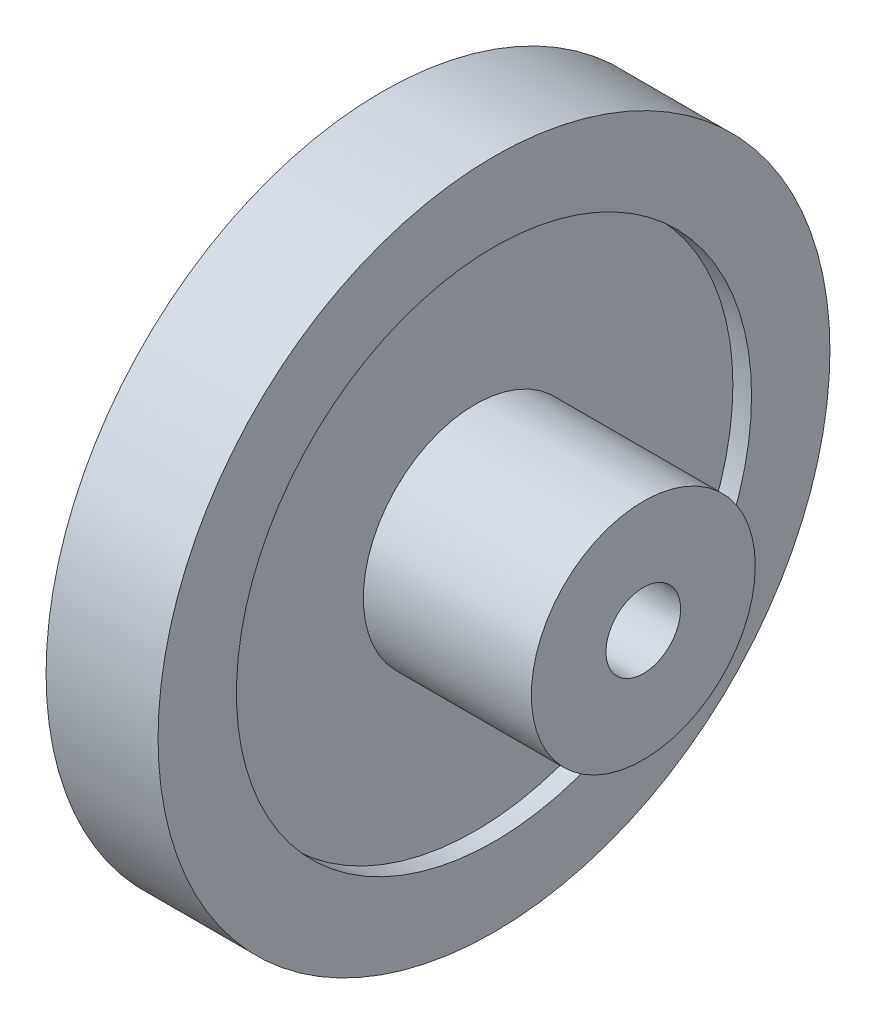
SolidWorks part; units mm, degrees
ref_plane "Plan de face" through (0, 0, 0) normal (0, 0, 1) x (1, 0, 0)
ref_plane "Plan de dessus" through (0, 0, 0) normal (0, 1, 0) x (1, 0, 0)
ref_plane "Plan de droite" through (0, 0, 0) normal (1, 0, 0) x (0, 0, -1)
sketch "Esquisse2" plane through (0, 0, 0) normal (1, 0, 0) x (0, 0, -1)
  arc A0 (8.9927, 0.363) -> (8.9699, 0.736) centre (0, 0) ccw
  arc A1 (8.7729, 2.0092) -> (8.6819, 2.3717) centre (0, 0) ccw
  arc A2 (8.2543, 3.587) -> (8.0983, 3.9266) centre (0, 0) ccw
  arc A3 (7.4547, 5.0426) -> (7.2389, 5.3478) centre (0, 0) ccw
  arc A4 (6.4012, 6.3266) -> (6.133, 6.5869) centre (0, 0) ccw
  arc A5 (5.1297, 7.395) -> (4.8182, 7.6016) centre (0, 0) ccw
  arc A6 (3.6835, 8.2117) -> (3.3394, 8.3575) centre (0, 0) ccw
  arc A7 (2.1119, 8.7487) -> (1.7468, 8.8289) centre (0, 0) ccw
  arc A8 (0.4683, 8.9878) -> (0.0948, 8.9995) centre (0, 0) ccw
  arc A9 (-1.1911, 8.9208) -> (-1.5605, 8.8637) centre (0, 0) ccw
  arc A10 (-2.8101, 8.5501) -> (-3.1626, 8.426) centre (0, 0) ccw
  arc A11 (-4.3333, 7.8881) -> (-4.657, 7.7014) centre (0, 0) ccw
  arc A12 (-5.7089, 6.9576) -> (-5.9929, 6.7146) centre (0, 0) ccw
  arc A13 (-6.8902, 5.7901) -> (-7.1246, 5.499) centre (0, 0) ccw
  arc A14 (-7.8368, 4.4254) -> (-8.0138, 4.0963) centre (0, 0) ccw
  arc A15 (-8.5165, 2.9101) -> (-8.63, 2.554) centre (0, 0) ccw
  arc A16 (-8.9063, 1.2956) -> (-8.9524, 0.9247) centre (0, 0) ccw
  arc A17 (-8.9927, -0.363) -> (-8.9699, -0.736) centre (0, 0) ccw
  arc A18 (-8.7729, -2.0092) -> (-8.6819, -2.3717) centre (0, 0) ccw
  arc A19 (-8.2543, -3.587) -> (-8.0983, -3.9266) centre (0, 0) ccw
  arc A20 (-7.4547, -5.0426) -> (-7.2389, -5.3478) centre (0, 0) ccw
  arc A21 (-6.4012, -6.3266) -> (-6.133, -6.5869) centre (0, 0) ccw
  arc A22 (-5.1297, -7.395) -> (-4.8182, -7.6016) centre (0, 0) ccw
  arc A23 (-3.6835, -8.2117) -> (-3.3394, -8.3575) centre (0, 0) ccw
  arc A24 (-2.1119, -8.7487) -> (-1.7468, -8.8289) centre (0, 0) ccw
  arc A25 (-0.4683, -8.9878) -> (-0.0948, -8.9995) centre (0, 0) ccw
  arc A26 (1.1911, -8.9208) -> (1.5605, -8.8637) centre (0, 0) ccw
  arc A27 (2.8101, -8.5501) -> (3.1626, -8.426) centre (0, 0) ccw
  arc A28 (4.3333, -7.8881) -> (4.657, -7.7014) centre (0, 0) ccw
  arc A29 (5.7089, -6.9576) -> (5.9929, -6.7146) centre (0, 0) ccw
  arc A30 (6.8902, -5.7901) -> (7.1246, -5.499) centre (0, 0) ccw
  arc A31 (7.8368, -4.4254) -> (8.0138, -4.0963) centre (0, 0) ccw
  arc A32 (8.5165, -2.9101) -> (8.63, -2.554) centre (0, 0) ccw
  arc A33 (8.9063, -1.2956) -> (8.9524, -0.9247) centre (0, 0) ccw
  arc A34 (7.987, 0) -> (7.8742, -0.1109) centre (7.9867, -0.1125) ccw
  arc A35 (7.8657, -0.3818) -> (7.9719, -0.4996) centre (7.9781, -0.3873) ccw
  arc A36 (7.8657, -0.3818) -> (7.8742, -0.1109) centre (0, 0) ccw
  arc A37 (7.851, 1.4676) -> (7.7605, 1.3379) centre (7.8714, 1.357) ccw
  arc A38 (7.802, 1.07) -> (7.928, 0.9737) centre (7.9134, 1.0853) ccw
  arc A39 (7.802, 1.07) -> (7.7605, 1.3379) centre (0, 0) ccw
  arc A40 (7.4477, 2.8852) -> (7.3826, 2.7411) centre (7.488, 2.7802) ccw
  arc A41 (7.4725, 2.4854) -> (7.6141, 2.4139) centre (7.5793, 2.5209) ccw
  arc A42 (7.4725, 2.4854) -> (7.3826, 2.7411) centre (0, 0) ccw
  arc A43 (6.7907, 4.2046) -> (6.7532, 4.0509) centre (6.8497, 4.1088) ccw
  arc A44 (6.8886, 3.8161) -> (7.0409, 3.7719) centre (6.987, 3.8706) ccw
  arc A45 (6.8886, 3.8161) -> (6.7532, 4.0509) centre (0, 0) ccw
  arc A46 (5.9025, 5.3808) -> (5.8938, 5.2229) centre (5.978, 5.2975) ccw
  arc A47 (6.0701, 5.0169) -> (6.2279, 5.0014) centre (6.1568, 5.0886) ccw
  arc A48 (6.0701, 5.0169) -> (5.8938, 5.2229) centre (0, 0) ccw
  arc A49 (4.8132, 6.3738) -> (4.8338, 6.2169) centre (4.9028, 6.3057) ccw
  arc A50 (5.0449, 6.0469) -> (5.2029, 6.0607) centre (5.117, 6.1333) ccw
  arc A51 (5.0449, 6.0469) -> (4.8338, 6.2169) centre (0, 0) ccw
  arc A52 (3.5601, 7.1497) -> (3.6091, 6.9993) centre (3.6607, 7.0993) ccw
  arc A53 (3.8479, 6.8709) -> (4.0007, 6.9135) centre (3.9028, 6.9691) ccw
  arc A54 (3.8479, 6.8709) -> (3.6091, 6.9993) centre (0, 0) ccw
  arc A55 (2.1857, 7.6821) -> (2.2616, 7.5433) centre (2.2939, 7.651) ccw
  arc A56 (2.5198, 7.461) -> (2.6622, 7.5309) centre (2.5558, 7.5676) ccw
  arc A57 (2.5198, 7.461) -> (2.2616, 7.5433) centre (0, 0) ccw
  arc A58 (0.7369, 7.9529) -> (0.837, 7.8304) centre (0.8489, 7.9423) ccw
  arc A59 (1.106, 7.797) -> (1.2331, 7.8918) centre (1.1218, 7.9083) ccw
  arc A60 (1.106, 7.797) -> (0.837, 7.8304) centre (0, 0) ccw
  arc A61 (-0.7369, 7.9529) -> (-0.6161, 7.8509) centre (-0.6249, 7.963) ccw
  arc A62 (-0.3455, 7.8674) -> (-0.2381, 7.984) centre (-0.3505, 7.9798) ccw
  arc A63 (-0.3455, 7.8674) -> (-0.6161, 7.8509) centre (0, 0) ccw
  arc A64 (-2.1857, 7.6821) -> (-2.0482, 7.604) centre (-2.0775, 7.7126) ccw
  arc A65 (-1.7853, 7.67) -> (-1.7011, 7.8044) centre (-1.8108, 7.7795) ccw
  arc A66 (-1.7853, 7.67) -> (-2.0482, 7.604) centre (0, 0) ccw
  arc A67 (-3.5601, 7.1497) -> (-3.4106, 7.0981) centre (-3.4593, 7.1996) ccw
  arc A68 (-3.1642, 7.2113) -> (-3.1062, 7.3589) centre (-3.2095, 7.3143) ccw
  arc A69 (-3.1642, 7.2113) -> (-3.4106, 7.0981) centre (0, 0) ccw
  arc A70 (-4.8132, 6.3738) -> (-4.6568, 6.3506) centre (-4.7233, 6.4413) ccw
  arc A71 (-4.4354, 6.5071) -> (-4.4055, 6.6628) centre (-4.4988, 6.6001) ccw
  arc A72 (-4.4354, 6.5071) -> (-4.6568, 6.3506) centre (0, 0) ccw
  arc A73 (-5.9025, 5.3808) -> (-5.7444, 5.3868) centre (-5.8265, 5.4637) ccw
  arc A74 (-5.5556, 5.5813) -> (-5.5547, 5.7399) centre (-5.635, 5.661) ccw
  arc A75 (-5.5556, 5.5813) -> (-5.7444, 5.3868) centre (0, 0) ccw
  arc A76 (-6.7907, 4.2046) -> (-6.6364, 4.2395) centre (-6.7312, 4.3001) ccw
  arc A77 (-6.4866, 4.4654) -> (-6.5149, 4.6215) centre (-6.5792, 4.5292) ccw
  arc A78 (-6.4866, 4.4654) -> (-6.6364, 4.2395) centre (0, 0) ccw
  arc A79 (-7.4477, 2.8852) -> (-7.3024, 2.9479) centre (-7.4067, 2.99) ccw
  arc A80 (-7.1966, 3.1975) -> (-7.2531, 3.3457) centre (-7.2995, 3.2432) ccw
  arc A81 (-7.1966, 3.1975) -> (-7.3024, 2.9479) centre (0, 0) ccw
  arc A82 (-7.851, 1.4676) -> (-7.7198, 1.5559) centre (-7.83, 1.5781) ccw
  arc A83 (-7.6616, 1.8207) -> (-7.7444, 1.956) centre (-7.7711, 1.8467) ccw
  arc A84 (-7.6616, 1.8207) -> (-7.7198, 1.5559) centre (0, 0) ccw
  arc A85 (-7.987, 0) -> (-7.8742, 0.1109) centre (-7.9867, 0.1125) ccw
  arc A86 (-7.8657, 0.3818) -> (-7.9719, 0.4996) centre (-7.9781, 0.3873) ccw
  arc A87 (-7.8657, 0.3818) -> (-7.8742, 0.1109) centre (0, 0) ccw
  arc A88 (-7.851, -1.4676) -> (-7.7605, -1.3379) centre (-7.8714, -1.357) ccw
  arc A89 (-7.802, -1.07) -> (-7.928, -0.9737) centre (-7.9134, -1.0853) ccw
  arc A90 (-7.802, -1.07) -> (-7.7605, -1.3379) centre (0, 0) ccw
  arc A91 (-7.4477, -2.8852) -> (-7.3826, -2.7411) centre (-7.488, -2.7802) ccw
  arc A92 (-7.4725, -2.4854) -> (-7.6141, -2.4139) centre (-7.5793, -2.5209) ccw
  arc A93 (-7.4725, -2.4854) -> (-7.3826, -2.7411) centre (0, 0) ccw
  arc A94 (-6.7907, -4.2046) -> (-6.7532, -4.0509) centre (-6.8497, -4.1088) ccw
  arc A95 (-6.8886, -3.8161) -> (-7.0409, -3.7719) centre (-6.987, -3.8706) ccw
  arc A96 (-6.8886, -3.8161) -> (-6.7532, -4.0509) centre (0, 0) ccw
  arc A97 (-5.9025, -5.3808) -> (-5.8938, -5.2229) centre (-5.978, -5.2975) ccw
  arc A98 (-6.0701, -5.0169) -> (-6.2279, -5.0014) centre (-6.1568, -5.0886) ccw
  arc A99 (-6.0701, -5.0169) -> (-5.8938, -5.2229) centre (0, 0) ccw
  arc A100 (-4.8132, -6.3738) -> (-4.8338, -6.2169) centre (-4.9028, -6.3057) ccw
  arc A101 (-5.0449, -6.0469) -> (-5.2029, -6.0607) centre (-5.117, -6.1333) ccw
  arc A102 (-5.0449, -6.0469) -> (-4.8338, -6.2169) centre (0, 0) ccw
  arc A103 (-3.5601, -7.1497) -> (-3.6091, -6.9993) centre (-3.6607, -7.0993) ccw
  arc A104 (-3.8479, -6.8709) -> (-4.0007, -6.9135) centre (-3.9028, -6.9691) ccw
  arc A105 (-3.8479, -6.8709) -> (-3.6091, -6.9993) centre (0, 0) ccw
  arc A106 (-2.1857, -7.6821) -> (-2.2616, -7.5433) centre (-2.2939, -7.651) ccw
  arc A107 (-2.5198, -7.461) -> (-2.6622, -7.5309) centre (-2.5558, -7.5676) ccw
  arc A108 (-2.5198, -7.461) -> (-2.2616, -7.5433) centre (0, 0) ccw
  arc A109 (-0.7369, -7.9529) -> (-0.837, -7.8304) centre (-0.8489, -7.9423) ccw
  arc A110 (-1.106, -7.797) -> (-1.2331, -7.8918) centre (-1.1218, -7.9083) ccw
  arc A111 (-1.106, -7.797) -> (-0.837, -7.8304) centre (0, 0) ccw
  arc A112 (0.7369, -7.9529) -> (0.6161, -7.8509) centre (0.6249, -7.963) ccw
  arc A113 (0.3455, -7.8674) -> (0.2381, -7.984) centre (0.3505, -7.9798) ccw
  arc A114 (0.3455, -7.8674) -> (0.6161, -7.8509) centre (0, 0) ccw
  arc A115 (2.1857, -7.6821) -> (2.0482, -7.604) centre (2.0775, -7.7126) ccw
  arc A116 (1.7853, -7.67) -> (1.7011, -7.8044) centre (1.8108, -7.7795) ccw
  arc A117 (1.7853, -7.67) -> (2.0482, -7.604) centre (0, 0) ccw
  arc A118 (3.5601, -7.1497) -> (3.4106, -7.0981) centre (3.4593, -7.1996) ccw
  arc A119 (3.1642, -7.2113) -> (3.1062, -7.3589) centre (3.2095, -7.3143) ccw
  arc A120 (3.1642, -7.2113) -> (3.4106, -7.0981) centre (0, 0) ccw
  arc A121 (4.8132, -6.3738) -> (4.6568, -6.3506) centre (4.7233, -6.4413) ccw
  arc A122 (4.4354, -6.5071) -> (4.4055, -6.6628) centre (4.4988, -6.6001) ccw
  arc A123 (4.4354, -6.5071) -> (4.6568, -6.3506) centre (0, 0) ccw
  arc A124 (5.9025, -5.3808) -> (5.7444, -5.3868) centre (5.8265, -5.4637) ccw
  arc A125 (5.5556, -5.5813) -> (5.5547, -5.7399) centre (5.635, -5.661) ccw
  arc A126 (5.5556, -5.5813) -> (5.7444, -5.3868) centre (0, 0) ccw
  arc A127 (6.7907, -4.2046) -> (6.6364, -4.2395) centre (6.7312, -4.3001) ccw
  arc A128 (6.4866, -4.4654) -> (6.5149, -4.6215) centre (6.5792, -4.5292) ccw
  arc A129 (6.4866, -4.4654) -> (6.6364, -4.2395) centre (0, 0) ccw
  arc A130 (7.4477, -2.8852) -> (7.3024, -2.9479) centre (7.4067, -2.99) ccw
  arc A131 (7.1966, -3.1975) -> (7.2531, -3.3457) centre (7.2995, -3.2432) ccw
  arc A132 (7.1966, -3.1975) -> (7.3024, -2.9479) centre (0, 0) ccw
  arc A133 (7.851, -1.4676) -> (7.7198, -1.5559) centre (7.83, -1.5781) ccw
  arc A134 (7.6616, -1.8207) -> (7.7444, -1.956) centre (7.7711, -1.8467) ccw
  arc A135 (7.6616, -1.8207) -> (7.7198, -1.5559) centre (0, 0) ccw
  circle A136 centre (0, 0) radius 1
  spline S0 degree 3 poles (7.987, 0) (8.0286, 0) (8.2037, 0.0282) (8.4818, 0.1115) (8.7713, 0.2415) (8.9323, 0.3284) (8.9927, 0.363) knots 0 0 0 0 0.124841 0.528779 0.867842 1.076016 1.076016 1.076016 1.076016
  spline S1 degree 3 poles (7.928, 0.9737) (7.9687, 0.9787) (8.146, 0.9721) (8.4321, 0.9233) (8.7354, 0.8295) (8.9058, 0.7629) (8.9699, 0.736) knots 0 0 0 0 0.124841 0.528779 0.867842 1.076016 1.076016 1.076016 1.076016
  spline S2 degree 3 poles (7.851, 1.4676) (7.8919, 1.4753) (8.0589, 1.5352) (8.3169, 1.6682) (8.5776, 1.8491) (8.7199, 1.9642) (8.7729, 2.0092) knots 0 0 0 0 0.124841 0.528779 0.867842 1.076016 1.076016 1.076016 1.076016
  spline S3 degree 3 poles (7.6141, 2.4139) (7.6532, 2.4263) (7.8287, 2.4523) (8.1189, 2.4569) (8.4342, 2.4205) (8.6139, 2.3863) (8.6819, 2.3717) knots 0 0 0 0 0.124841 0.528779 0.867842 1.076016 1.076016 1.076016 1.076016
  spline S4 degree 3 poles (7.4477, 2.8852) (7.4865, 2.9003) (7.6396, 2.9898) (7.8687, 3.168) (8.0918, 3.3938) (8.2105, 3.533) (8.2543, 3.587) knots 0 0 0 0 0.124841 0.528779 0.867842 1.076016 1.076016 1.076016 1.076016
  spline S5 degree 3 poles (7.0409, 3.7719) (7.0771, 3.7913) (7.2448, 3.8491) (7.5292, 3.9069) (7.8458, 3.9291) (8.0288, 3.9285) (8.0983, 3.9266) knots 0 0 0 0 0.124841 0.528779 0.867842 1.076016 1.076016 1.076016 1.076016
  spline S6 degree 3 poles (6.7907, 4.2046) (6.8261, 4.2265) (6.9601, 4.3427) (7.1526, 4.5599) (7.3304, 4.8229) (7.4215, 4.9815) (7.4547, 5.0426) knots 0 0 0 0 0.124841 0.528779 0.867842 1.076016 1.076016 1.076016 1.076016
  spline S7 degree 3 poles (6.2279, 5.0014) (6.2599, 5.0271) (6.4141, 5.1148) (6.6831, 5.2239) (6.9903, 5.3039) (7.1702, 5.3369) (7.2389, 5.3478) knots 0 0 0 0 0.124841 0.528779 0.867842 1.076016 1.076016 1.076016 1.076016
  spline S8 degree 3 poles (5.9025, 5.3808) (5.9332, 5.4088) (6.0436, 5.5477) (6.193, 5.7966) (6.3194, 6.0877) (6.3798, 6.2604) (6.4012, 6.3266) knots 0 0 0 0 0.124841 0.528779 0.867842 1.076016 1.076016 1.076016 1.076016
  spline S9 degree 3 poles (5.2029, 6.0607) (5.2296, 6.0918) (5.3651, 6.2063) (5.6094, 6.363) (5.8967, 6.498) (6.0675, 6.5636) (6.133, 6.5869) knots 0 0 0 0 0.124841 0.528779 0.867842 1.076016 1.076016 1.076016 1.076016
  spline S10 degree 3 poles (4.8132, 6.3738) (4.8383, 6.407) (4.9213, 6.5637) (5.0224, 6.8358) (5.0932, 7.1452) (5.1208, 7.3261) (5.1297, 7.395) knots 0 0 0 0 0.124841 0.528779 0.867842 1.076016 1.076016 1.076016 1.076016
  spline S11 degree 3 poles (4.0007, 6.9135) (4.0212, 6.949) (4.1333, 7.0864) (4.3447, 7.2854) (4.6022, 7.4709) (4.7581, 7.5667) (4.8182, 7.6016) knots 0 0 0 0 0.124841 0.528779 0.867842 1.076016 1.076016 1.076016 1.076016
  spline S12 degree 3 poles (3.5601, 7.1497) (3.5787, 7.1869) (3.6315, 7.3563) (3.6808, 7.6423) (3.6935, 7.9594) (3.6875, 8.1423) (3.6835, 8.2117) knots 0 0 0 0 0.124841 0.528779 0.867842 1.076016 1.076016 1.076016 1.076016
  spline S13 degree 3 poles (2.6622, 7.5309) (2.6759, 7.5696) (2.7608, 7.7253) (2.932, 7.9596) (3.1511, 8.1893) (3.2867, 8.3122) (3.3394, 8.3575) knots 0 0 0 0 0.124841 0.528779 0.867842 1.076016 1.076016 1.076016 1.076016
  spline S14 degree 3 poles (2.1857, 7.6821) (2.1971, 7.7221) (2.2179, 7.8983) (2.2139, 8.1885) (2.1681, 8.5026) (2.1286, 8.6812) (2.1119, 8.7487) knots 0 0 0 0 0.124841 0.528779 0.867842 1.076016 1.076016 1.076016 1.076016
  spline S15 degree 3 poles (1.2331, 7.8918) (1.2394, 7.9324) (1.2943, 8.101) (1.4195, 8.3629) (1.5927, 8.6289) (1.7034, 8.7746) (1.7468, 8.8289) knots 0 0 0 0 0.124841 0.528779 0.867842 1.076016 1.076016 1.076016 1.076016
  spline S16 degree 3 poles (0.7369, 7.9529) (0.7408, 7.9944) (0.7288, 8.1713) (0.6715, 8.4559) (0.5688, 8.7562) (0.4971, 8.9245) (0.4683, 8.9878) knots 0 0 0 0 0.124841 0.528779 0.867842 1.076016 1.076016 1.076016 1.076016
  spline S17 degree 3 poles (-0.2381, 7.984) (-0.2393, 8.025) (-0.2163, 8.2009) (-0.1413, 8.4813) (-0.02, 8.7746) (0.0621, 8.9382) (0.0948, 8.9995) knots 0 0 0 0 0.124841 0.528779 0.867842 1.076016 1.076016 1.076016 1.076016
  spline S18 degree 3 poles (-0.7369, 7.9529) (-0.7408, 7.9944) (-0.785, 8.1661) (-0.8937, 8.4353) (-1.0498, 8.7116) (-1.1512, 8.8639) (-1.1911, 8.9208) knots 0 0 0 0 0.124841 0.528779 0.867842 1.076016 1.076016 1.076016 1.076016
  spline S19 degree 3 poles (-1.7011, 7.8044) (-1.7098, 7.8444) (-1.7195, 8.0216) (-1.6973, 8.311) (-1.632, 8.6216) (-1.5814, 8.7974) (-1.5605, 8.8637) knots 0 0 0 0 0.124841 0.528779 0.867842 1.076016 1.076016 1.076016 1.076016
  spline S20 degree 3 poles (-2.1857, 7.6821) (-2.1971, 7.7221) (-2.2722, 7.8828) (-2.4284, 8.1275) (-2.6327, 8.3704) (-2.7603, 8.5015) (-2.8101, 8.5501) knots 0 0 0 0 0.124841 0.528779 0.867842 1.076016 1.076016 1.076016 1.076016
  spline S21 degree 3 poles (-3.1062, 7.3589) (-3.1221, 7.3967) (-3.1642, 7.569) (-3.1956, 7.8576) (-3.1884, 8.1749) (-3.171, 8.357) (-3.1626, 8.426) knots 0 0 0 0 0.124841 0.528779 0.867842 1.076016 1.076016 1.076016 1.076016
  spline S22 degree 3 poles (-3.5601, 7.1497) (-3.5787, 7.1869) (-3.682, 7.3311) (-3.8805, 7.5429) (-4.1259, 7.7441) (-4.2755, 7.8495) (-4.3333, 7.8881) knots 0 0 0 0 0.124841 0.528779 0.867842 1.076016 1.076016 1.076016 1.076016
  spline S23 degree 3 poles (-4.4055, 6.6628) (-4.4281, 6.6971) (-4.5011, 6.8587) (-4.585, 7.1366) (-4.6363, 7.4498) (-4.6526, 7.6321) (-4.657, 7.7014) knots 0 0 0 0 0.124841 0.528779 0.867842 1.076016 1.076016 1.076016 1.076016
  spline S24 degree 3 poles (-4.8132, 6.3738) (-4.8383, 6.407) (-4.9664, 6.5297) (-5.2004, 6.7014) (-5.4787, 6.8541) (-5.645, 6.9302) (-5.7089, 6.9576) knots 0 0 0 0 0.124841 0.528779 0.867842 1.076016 1.076016 1.076016 1.076016
  spline S25 degree 3 poles (-5.5547, 5.7399) (-5.5833, 5.7694) (-5.6848, 5.9148) (-5.8183, 6.1726) (-5.9262, 6.4711) (-5.9757, 6.6472) (-5.9929, 6.7146) knots 0 0 0 0 0.124841 0.528779 0.867842 1.076016 1.076016 1.076016 1.076016
  spline S26 degree 3 poles (-5.9025, 5.3808) (-5.9332, 5.4088) (-6.0816, 5.506) (-6.3432, 5.6317) (-6.6448, 5.7307) (-6.8223, 5.775) (-6.8902, 5.7901) knots 0 0 0 0 0.124841 0.528779 0.867842 1.076016 1.076016 1.076016 1.076016
  spline S27 degree 3 poles (-6.5149, 4.6215) (-6.5483, 4.6452) (-6.6748, 4.7696) (-6.8534, 4.9984) (-7.0144, 5.2719) (-7.0954, 5.436) (-7.1246, 5.499) knots 0 0 0 0 0.124841 0.528779 0.867842 1.076016 1.076016 1.076016 1.076016
  spline S28 degree 3 poles (-6.7907, 4.2046) (-6.8261, 4.2265) (-6.9898, 4.2947) (-7.2701, 4.3703) (-7.5847, 4.4122) (-7.7673, 4.423) (-7.8368, 4.4254) knots 0 0 0 0 0.124841 0.528779 0.867842 1.076016 1.076016 1.076016 1.076016
  spline S29 degree 3 poles (-7.2531, 3.3457) (-7.2904, 3.3629) (-7.4376, 3.4619) (-7.6552, 3.654) (-7.8637, 3.8933) (-7.9735, 4.0396) (-8.0138, 4.0963) knots 0 0 0 0 0.124841 0.528779 0.867842 1.076016 1.076016 1.076016 1.076016
  spline S30 degree 3 poles (-7.4477, 2.8852) (-7.4865, 2.9003) (-7.66, 2.9372) (-7.9493, 2.96) (-8.2663, 2.9434) (-8.4478, 2.9205) (-8.5165, 2.9101) knots 0 0 0 0 0.124841 0.528779 0.867842 1.076016 1.076016 1.076016 1.076016
  spline S31 degree 3 poles (-7.7444, 1.956) (-7.7842, 1.966) (-7.9471, 2.0363) (-8.1962, 2.1851) (-8.4452, 2.3821) (-8.58, 2.5057) (-8.63, 2.554) knots 0 0 0 0 0.124841 0.528779 0.867842 1.076016 1.076016 1.076016 1.076016
  spline S32 degree 3 poles (-7.851, 1.4676) (-7.8919, 1.4753) (-8.0692, 1.4797) (-8.3578, 1.4489) (-8.6664, 1.3743) (-8.8406, 1.3185) (-8.9063, 1.2956) knots 0 0 0 0 0.124841 0.528779 0.867842 1.076016 1.076016 1.076016 1.076016
  spline S33 degree 3 poles (-7.9719, 0.4996) (-8.0129, 0.5022) (-8.1859, 0.5413) (-8.4582, 0.6419) (-8.7391, 0.7897) (-8.8943, 0.8865) (-8.9524, 0.9247) knots 0 0 0 0 0.124841 0.528779 0.867842 1.076016 1.076016 1.076016 1.076016
  spline S34 degree 3 poles (-7.987, 0) (-8.0286, 0) (-8.2037, -0.0282) (-8.4818, -0.1115) (-8.7713, -0.2415) (-8.9323, -0.3284) (-8.9927, -0.363) knots 0 0 0 0 0.124841 0.528779 0.867842 1.076016 1.076016 1.076016 1.076016
  spline S35 degree 3 poles (-7.928, -0.9737) (-7.9687, -0.9787) (-8.146, -0.9721) (-8.4321, -0.9233) (-8.7354, -0.8295) (-8.9058, -0.7629) (-8.9699, -0.736) knots 0 0 0 0 0.124841 0.528779 0.867842 1.076016 1.076016 1.076016 1.076016
  spline S36 degree 3 poles (-7.851, -1.4676) (-7.8919, -1.4753) (-8.0589, -1.5352) (-8.3169, -1.6682) (-8.5776, -1.8491) (-8.7199, -1.9642) (-8.7729, -2.0092) knots 0 0 0 0 0.124841 0.528779 0.867842 1.076016 1.076016 1.076016 1.076016
  spline S37 degree 3 poles (-7.6141, -2.4139) (-7.6532, -2.4263) (-7.8287, -2.4523) (-8.1189, -2.4569) (-8.4342, -2.4205) (-8.6139, -2.3863) (-8.6819, -2.3717) knots 0 0 0 0 0.124841 0.528779 0.867842 1.076016 1.076016 1.076016 1.076016
  spline S38 degree 3 poles (-7.4477, -2.8852) (-7.4865, -2.9003) (-7.6396, -2.9898) (-7.8687, -3.168) (-8.0918, -3.3938) (-8.2105, -3.533) (-8.2543, -3.587) knots 0 0 0 0 0.124841 0.528779 0.867842 1.076016 1.076016 1.076016 1.076016
  spline S39 degree 3 poles (-7.0409, -3.7719) (-7.0771, -3.7913) (-7.2448, -3.8491) (-7.5292, -3.9069) (-7.8458, -3.9291) (-8.0288, -3.9285) (-8.0983, -3.9266) knots 0 0 0 0 0.124841 0.528779 0.867842 1.076016 1.076016 1.076016 1.076016
  spline S40 degree 3 poles (-6.7907, -4.2046) (-6.8261, -4.2265) (-6.9601, -4.3427) (-7.1526, -4.5599) (-7.3304, -4.8229) (-7.4215, -4.9815) (-7.4547, -5.0426) knots 0 0 0 0 0.124841 0.528779 0.867842 1.076016 1.076016 1.076016 1.076016
  spline S41 degree 3 poles (-6.2279, -5.0014) (-6.2599, -5.0271) (-6.4141, -5.1148) (-6.6831, -5.2239) (-6.9903, -5.3039) (-7.1702, -5.3369) (-7.2389, -5.3478) knots 0 0 0 0 0.124841 0.528779 0.867842 1.076016 1.076016 1.076016 1.076016
  spline S42 degree 3 poles (-5.9025, -5.3808) (-5.9332, -5.4088) (-6.0436, -5.5477) (-6.193, -5.7966) (-6.3194, -6.0877) (-6.3798, -6.2604) (-6.4012, -6.3266) knots 0 0 0 0 0.124841 0.528779 0.867842 1.076016 1.076016 1.076016 1.076016
  spline S43 degree 3 poles (-5.2029, -6.0607) (-5.2296, -6.0918) (-5.3651, -6.2063) (-5.6094, -6.363) (-5.8967, -6.498) (-6.0675, -6.5636) (-6.133, -6.5869) knots 0 0 0 0 0.124841 0.528779 0.867842 1.076016 1.076016 1.076016 1.076016
  spline S44 degree 3 poles (-4.8132, -6.3738) (-4.8383, -6.407) (-4.9213, -6.5637) (-5.0224, -6.8358) (-5.0932, -7.1452) (-5.1208, -7.3261) (-5.1297, -7.395) knots 0 0 0 0 0.124841 0.528779 0.867842 1.076016 1.076016 1.076016 1.076016
  spline S45 degree 3 poles (-4.0007, -6.9135) (-4.0212, -6.949) (-4.1333, -7.0864) (-4.3447, -7.2854) (-4.6022, -7.4709) (-4.7581, -7.5667) (-4.8182, -7.6016) knots 0 0 0 0 0.124841 0.528779 0.867842 1.076016 1.076016 1.076016 1.076016
  spline S46 degree 3 poles (-3.5601, -7.1497) (-3.5787, -7.1869) (-3.6315, -7.3563) (-3.6808, -7.6423) (-3.6935, -7.9594) (-3.6875, -8.1423) (-3.6835, -8.2117) knots 0 0 0 0 0.124841 0.528779 0.867842 1.076016 1.076016 1.076016 1.076016
  spline S47 degree 3 poles (-2.6622, -7.5309) (-2.6759, -7.5696) (-2.7608, -7.7253) (-2.932, -7.9596) (-3.1511, -8.1893) (-3.2867, -8.3122) (-3.3394, -8.3575) knots 0 0 0 0 0.124841 0.528779 0.867842 1.076016 1.076016 1.076016 1.076016
  spline S48 degree 3 poles (-2.1857, -7.6821) (-2.1971, -7.7221) (-2.2179, -7.8983) (-2.2139, -8.1885) (-2.1681, -8.5026) (-2.1286, -8.6812) (-2.1119, -8.7487) knots 0 0 0 0 0.124841 0.528779 0.867842 1.076016 1.076016 1.076016 1.076016
  spline S49 degree 3 poles (-1.2331, -7.8918) (-1.2394, -7.9324) (-1.2943, -8.101) (-1.4195, -8.3629) (-1.5927, -8.6289) (-1.7034, -8.7746) (-1.7468, -8.8289) knots 0 0 0 0 0.124841 0.528779 0.867842 1.076016 1.076016 1.076016 1.076016
  spline S50 degree 3 poles (-0.7369, -7.9529) (-0.7408, -7.9944) (-0.7288, -8.1713) (-0.6715, -8.4559) (-0.5688, -8.7562) (-0.4971, -8.9245) (-0.4683, -8.9878) knots 0 0 0 0 0.124841 0.528779 0.867842 1.076016 1.076016 1.076016 1.076016
  spline S51 degree 3 poles (0.2381, -7.984) (0.2393, -8.025) (0.2163, -8.2009) (0.1413, -8.4813) (0.02, -8.7746) (-0.0621, -8.9382) (-0.0948, -8.9995) knots 0 0 0 0 0.124841 0.528779 0.867842 1.076016 1.076016 1.076016 1.076016
  spline S52 degree 3 poles (0.7369, -7.9529) (0.7408, -7.9944) (0.785, -8.1661) (0.8937, -8.4353) (1.0498, -8.7116) (1.1512, -8.8639) (1.1911, -8.9208) knots 0 0 0 0 0.124841 0.528779 0.867842 1.076016 1.076016 1.076016 1.076016
  spline S53 degree 3 poles (1.7011, -7.8044) (1.7098, -7.8444) (1.7195, -8.0216) (1.6973, -8.311) (1.632, -8.6216) (1.5814, -8.7974) (1.5605, -8.8637) knots 0 0 0 0 0.124841 0.528779 0.867842 1.076016 1.076016 1.076016 1.076016
  spline S54 degree 3 poles (2.1857, -7.6821) (2.1971, -7.7221) (2.2722, -7.8828) (2.4284, -8.1275) (2.6327, -8.3704) (2.7603, -8.5015) (2.8101, -8.5501) knots 0 0 0 0 0.124841 0.528779 0.867842 1.076016 1.076016 1.076016 1.076016
  spline S55 degree 3 poles (3.1062, -7.3589) (3.1221, -7.3967) (3.1642, -7.569) (3.1956, -7.8576) (3.1884, -8.1749) (3.171, -8.357) (3.1626, -8.426) knots 0 0 0 0 0.124841 0.528779 0.867842 1.076016 1.076016 1.076016 1.076016
  spline S56 degree 3 poles (3.5601, -7.1497) (3.5787, -7.1869) (3.682, -7.3311) (3.8805, -7.5429) (4.1259, -7.7441) (4.2755, -7.8495) (4.3333, -7.8881) knots 0 0 0 0 0.124841 0.528779 0.867842 1.076016 1.076016 1.076016 1.076016
  spline S57 degree 3 poles (4.4055, -6.6628) (4.4281, -6.6971) (4.5011, -6.8587) (4.585, -7.1366) (4.6363, -7.4498) (4.6526, -7.6321) (4.657, -7.7014) knots 0 0 0 0 0.124841 0.528779 0.867842 1.076016 1.076016 1.076016 1.076016
  spline S58 degree 3 poles (4.8132, -6.3738) (4.8383, -6.407) (4.9664, -6.5297) (5.2004, -6.7014) (5.4787, -6.8541) (5.645, -6.9302) (5.7089, -6.9576) knots 0 0 0 0 0.124841 0.528779 0.867842 1.076016 1.076016 1.076016 1.076016
  spline S59 degree 3 poles (5.5547, -5.7399) (5.5833, -5.7694) (5.6848, -5.9148) (5.8183, -6.1726) (5.9262, -6.4711) (5.9757, -6.6472) (5.9929, -6.7146) knots 0 0 0 0 0.124841 0.528779 0.867842 1.076016 1.076016 1.076016 1.076016
  spline S60 degree 3 poles (5.9025, -5.3808) (5.9332, -5.4088) (6.0816, -5.506) (6.3432, -5.6317) (6.6448, -5.7307) (6.8223, -5.775) (6.8902, -5.7901) knots 0 0 0 0 0.124841 0.528779 0.867842 1.076016 1.076016 1.076016 1.076016
  spline S61 degree 3 poles (6.5149, -4.6215) (6.5483, -4.6452) (6.6748, -4.7696) (6.8534, -4.9984) (7.0144, -5.2719) (7.0954, -5.436) (7.1246, -5.499) knots 0 0 0 0 0.124841 0.528779 0.867842 1.076016 1.076016 1.076016 1.076016
  spline S62 degree 3 poles (6.7907, -4.2046) (6.8261, -4.2265) (6.9898, -4.2947) (7.2701, -4.3703) (7.5847, -4.4122) (7.7673, -4.423) (7.8368, -4.4254) knots 0 0 0 0 0.124841 0.528779 0.867842 1.076016 1.076016 1.076016 1.076016
  spline S63 degree 3 poles (7.2531, -3.3457) (7.2904, -3.3629) (7.4376, -3.4619) (7.6552, -3.654) (7.8637, -3.8933) (7.9735, -4.0396) (8.0138, -4.0963) knots 0 0 0 0 0.124841 0.528779 0.867842 1.076016 1.076016 1.076016 1.076016
  spline S64 degree 3 poles (7.4477, -2.8852) (7.4865, -2.9003) (7.66, -2.9372) (7.9493, -2.96) (8.2663, -2.9434) (8.4478, -2.9205) (8.5165, -2.9101) knots 0 0 0 0 0.124841 0.528779 0.867842 1.076016 1.076016 1.076016 1.076016
  spline S65 degree 3 poles (7.7444, -1.956) (7.7842, -1.966) (7.9471, -2.0363) (8.1962, -2.1851) (8.4452, -2.3821) (8.58, -2.5057) (8.63, -2.554) knots 0 0 0 0 0.124841 0.528779 0.867842 1.076016 1.076016 1.076016 1.076016
  spline S66 degree 3 poles (7.851, -1.4676) (7.8919, -1.4753) (8.0692, -1.4797) (8.3578, -1.4489) (8.6664, -1.3743) (8.8406, -1.3185) (8.9063, -1.2956) knots 0 0 0 0 0.124841 0.528779 0.867842 1.076016 1.076016 1.076016 1.076016
  spline S67 degree 3 poles (7.9719, -0.4996) (8.0129, -0.5022) (8.1859, -0.5413) (8.4582, -0.6419) (8.7391, -0.7897) (8.8943, -0.8865) (8.9524, -0.9247) knots 0 0 0 0 0.124841 0.528779 0.867842 1.076016 1.076016 1.076016 1.076016
  dimension "D1" = 2
extrude "Boss.-Extru.1" add sketch "Esquisse2" along normal blind 3
sketch "Esquisse3" plane through (3, 0, 0) normal (1, 0, 0) x (0, 0, -1)
  circle A0 centre (0, 0) radius 6.9
  dimension "D1" = 13.8
extrude "Enlèv. mat.-Extru.1" cut sketch "Esquisse3" against normal blind 0.5
sketch "Esquisse4" plane through (2.5, 0, 0) normal (1, 0, 0) x (0, 0, -1)
  arc A0 (2.9773, 0.3683) -> (2.9271, 0.6573) centre (0, 0) ccw
  arc A1 (2.1922, 2.048) -> (1.9817, 2.2523) centre (0, 0) ccw
  arc A2 (0.5698, 2.9454) -> (0.2794, 2.987) centre (0, 0) ccw
  arc A3 (-1.2703, 2.7178) -> (-1.5297, 2.5807) centre (0, 0) ccw
  arc A4 (-2.6252, 1.4521) -> (-2.7544, 1.1887) centre (0, 0) ccw
  arc A5 (-2.9773, -0.3683) -> (-2.9271, -0.6573) centre (0, 0) ccw
  arc A6 (-2.1922, -2.048) -> (-1.9817, -2.2523) centre (0, 0) ccw
  arc A7 (-0.5698, -2.9454) -> (-0.2794, -2.987) centre (0, 0) ccw
  arc A8 (1.2703, -2.7178) -> (1.5297, -2.5807) centre (0, 0) ccw
  arc A9 (2.6252, -1.4521) -> (2.7544, -1.1887) centre (0, 0) ccw
  arc A10 (1.8368, -0.3764) -> (1.8687, -0.154) centre (0, 0) ccw
  arc A11 (1.7073, 0.7751) -> (1.6023, 0.9738) centre (0, 0) ccw
  arc A12 (0.9256, 1.6306) -> (0.7239, 1.7296) centre (0, 0) ccw
  arc A13 (-0.2096, 1.8632) -> (-0.431, 1.8248) centre (0, 0) ccw
  arc A14 (-1.2648, 1.3842) -> (-1.4213, 1.2229) centre (0, 0) ccw
  arc A15 (-1.8368, 0.3764) -> (-1.8687, 0.154) centre (0, 0) ccw
  arc A16 (-1.7073, -0.7751) -> (-1.6023, -0.9738) centre (0, 0) ccw
  arc A17 (-0.9256, -1.6306) -> (-0.7239, -1.7296) centre (0, 0) ccw
  arc A18 (0.2096, -1.8632) -> (0.431, -1.8248) centre (0, 0) ccw
  arc A19 (1.2648, -1.3842) -> (1.4213, -1.2229) centre (0, 0) ccw
  circle A20 centre (0, 0) radius 1
  spline S0 degree 3 poles (2.349, 0) (2.3611, 0) (2.4126, 0.0085) (2.4945, 0.0326) (2.6584, 0.1065) (2.823, 0.2207) (2.9394, 0.3292) (2.9773, 0.3683) knots 0 0 0 0 0.036251 0.155621 0.255291 0.575255 0.744085 0.744085 0.744085 0.744085
  spline S1 degree 3 poles (2.2114, 0.7921) (2.2228, 0.7962) (2.2741, 0.8056) (2.3594, 0.8105) (2.5386, 0.7962) (2.7321, 0.7442) (2.8782, 0.6813) (2.9271, 0.6573) knots 0 0 0 0 0.036251 0.155621 0.255291 0.575255 0.744085 0.744085 0.744085 0.744085
  spline S2 degree 3 poles (1.9004, 1.3807) (1.9102, 1.3878) (1.9469, 1.4249) (1.9989, 1.4926) (2.0881, 1.6487) (2.1541, 1.8379) (2.1845, 1.9941) (2.1922, 2.048) knots 0 0 0 0 0.036251 0.155621 0.255291 0.575255 0.744085 0.744085 0.744085 0.744085
  spline S3 degree 3 poles (1.3235, 1.9407) (1.3303, 1.9507) (1.3663, 1.9885) (1.4324, 2.0425) (1.5858, 2.1363) (1.7728, 2.2079) (1.9281, 2.243) (1.9817, 2.2523) knots 0 0 0 0 0.036251 0.155621 0.255291 0.575255 0.744085 0.744085 0.744085 0.744085
  spline S4 degree 3 poles (0.7259, 2.234) (0.7296, 2.2455) (0.7375, 2.2971) (0.7398, 2.3825) (0.7202, 2.5612) (0.6625, 2.753) (0.5952, 2.8973) (0.5698, 2.9454) knots 0 0 0 0 0.036251 0.155621 0.255291 0.575255 0.744085 0.744085 0.744085 0.744085
  spline S5 degree 3 poles (-0.07, 2.348) (-0.0704, 2.36) (-0.0634, 2.4118) (-0.0417, 2.4943) (0.0272, 2.6604) (0.1365, 2.8283) (0.2415, 2.9479) (0.2794, 2.987) knots 0 0 0 0 0.036251 0.155621 0.255291 0.575255 0.744085 0.744085 0.744085 0.744085
  spline S6 degree 3 poles (-0.7259, 2.234) (-0.7296, 2.2455) (-0.7536, 2.2919) (-0.8019, 2.3623) (-0.9228, 2.4954) (-1.0823, 2.6166) (-1.2215, 2.6938) (-1.2703, 2.7178) knots 0 0 0 0 0.036251 0.155621 0.255291 0.575255 0.744085 0.744085 0.744085 0.744085
  spline S7 degree 3 poles (-1.4367, 1.8584) (-1.4441, 1.8679) (-1.4689, 1.9139) (-1.4999, 1.9934) (-1.5417, 2.1683) (-1.552, 2.3684) (-1.5374, 2.5268) (-1.5297, 2.5807) knots 0 0 0 0 0.036251 0.155621 0.255291 0.575255 0.744085 0.744085 0.744085 0.744085
  spline S8 degree 3 poles (-1.9004, 1.3807) (-1.9102, 1.3878) (-1.9568, 1.4112) (-2.0373, 1.4398) (-2.2133, 1.4764) (-2.4136, 1.4808) (-2.5715, 1.4614) (-2.6252, 1.4521) knots 0 0 0 0 0.036251 0.155621 0.255291 0.575255 0.744085 0.744085 0.744085 0.744085
  spline S9 degree 3 poles (-2.2547, 0.659) (-2.2663, 0.6624) (-2.3133, 0.6849) (-2.3852, 0.7311) (-2.5218, 0.848) (-2.6477, 1.0038) (-2.729, 1.1406) (-2.7544, 1.1887) knots 0 0 0 0 0.036251 0.155621 0.255291 0.575255 0.744085 0.744085 0.744085 0.744085
  spline S10 degree 3 poles (-2.349, 0) (-2.3611, 0) (-2.4126, -0.0085) (-2.4945, -0.0326) (-2.6584, -0.1065) (-2.823, -0.2207) (-2.9394, -0.3292) (-2.9773, -0.3683) knots 0 0 0 0 0.036251 0.155621 0.255291 0.575255 0.744085 0.744085 0.744085 0.744085
  spline S11 degree 3 poles (-2.2114, -0.7921) (-2.2228, -0.7962) (-2.2741, -0.8056) (-2.3594, -0.8105) (-2.5386, -0.7962) (-2.7321, -0.7442) (-2.8782, -0.6813) (-2.9271, -0.6573) knots 0 0 0 0 0.036251 0.155621 0.255291 0.575255 0.744085 0.744085 0.744085 0.744085
  spline S12 degree 3 poles (-1.9004, -1.3807) (-1.9102, -1.3878) (-1.9469, -1.4249) (-1.9989, -1.4926) (-2.0881, -1.6487) (-2.1541, -1.8379) (-2.1845, -1.9941) (-2.1922, -2.048) knots 0 0 0 0 0.036251 0.155621 0.255291 0.575255 0.744085 0.744085 0.744085 0.744085
  spline S13 degree 3 poles (-1.3235, -1.9407) (-1.3303, -1.9507) (-1.3663, -1.9885) (-1.4324, -2.0425) (-1.5858, -2.1363) (-1.7728, -2.2079) (-1.9281, -2.243) (-1.9817, -2.2523) knots 0 0 0 0 0.036251 0.155621 0.255291 0.575255 0.744085 0.744085 0.744085 0.744085
  spline S14 degree 3 poles (-0.7259, -2.234) (-0.7296, -2.2455) (-0.7375, -2.2971) (-0.7398, -2.3825) (-0.7202, -2.5612) (-0.6625, -2.753) (-0.5952, -2.8973) (-0.5698, -2.9454) knots 0 0 0 0 0.036251 0.155621 0.255291 0.575255 0.744085 0.744085 0.744085 0.744085
  spline S15 degree 3 poles (0.07, -2.348) (0.0704, -2.36) (0.0634, -2.4118) (0.0417, -2.4943) (-0.0272, -2.6604) (-0.1365, -2.8283) (-0.2415, -2.9479) (-0.2794, -2.987) knots 0 0 0 0 0.036251 0.155621 0.255291 0.575255 0.744085 0.744085 0.744085 0.744085
  spline S16 degree 3 poles (0.7259, -2.234) (0.7296, -2.2455) (0.7536, -2.2919) (0.8019, -2.3623) (0.9228, -2.4954) (1.0823, -2.6166) (1.2215, -2.6938) (1.2703, -2.7178) knots 0 0 0 0 0.036251 0.155621 0.255291 0.575255 0.744085 0.744085 0.744085 0.744085
  spline S17 degree 3 poles (1.4367, -1.8584) (1.4441, -1.8679) (1.4689, -1.9139) (1.4999, -1.9934) (1.5417, -2.1683) (1.552, -2.3684) (1.5374, -2.5268) (1.5297, -2.5807) knots 0 0 0 0 0.036251 0.155621 0.255291 0.575255 0.744085 0.744085 0.744085 0.744085
  spline S18 degree 3 poles (1.9004, -1.3807) (1.9102, -1.3878) (1.9568, -1.4112) (2.0373, -1.4398) (2.2133, -1.4764) (2.4136, -1.4808) (2.5715, -1.4614) (2.6252, -1.4521) knots 0 0 0 0 0.036251 0.155621 0.255291 0.575255 0.744085 0.744085 0.744085 0.744085
  spline S19 degree 3 poles (2.2547, -0.659) (2.2663, -0.6624) (2.3133, -0.6849) (2.3852, -0.7311) (2.5218, -0.848) (2.6477, -1.0038) (2.729, -1.1406) (2.7544, -1.1887) knots 0 0 0 0 0.036251 0.155621 0.255291 0.575255 0.744085 0.744085 0.744085 0.744085
  spline S20 degree 3 poles (2.349, 0) (2.2648, 0) (2.1034, 0.0291) (1.8817, -0.0633) (1.8687, -0.154) knots 0 0 0 0 0.252618 0.527509 0.527509 0.527509 0.527509
  spline S21 degree 3 poles (2.2547, -0.659) (2.1739, -0.6353) (2.0108, -0.618) (1.8238, -0.4671) (1.8368, -0.3764) knots 0 0 0 0 0.252618 0.527509 0.527509 0.527509 0.527509
  spline S22 degree 3 poles (1.9004, 1.3807) (1.8323, 1.3312) (1.6846, 1.2599) (1.5595, 1.0548) (1.6023, 0.9738) knots 0 0 0 0 0.252618 0.527509 0.527509 0.527509 0.527509
  spline S23 degree 3 poles (2.2114, 0.7921) (2.1321, 0.7637) (1.99, 0.682) (1.7501, 0.6941) (1.7073, 0.7751) knots 0 0 0 0 0.252618 0.527509 0.527509 0.527509 0.527509
  spline S24 degree 3 poles (0.7259, 2.234) (0.6999, 2.1539) (0.6223, 2.0095) (0.6416, 1.77) (0.7239, 1.7296) knots 0 0 0 0 0.252618 0.527509 0.527509 0.527509 0.527509
  spline S25 degree 3 poles (1.3235, 1.9407) (1.276, 1.8711) (1.2091, 1.7214) (1.0079, 1.5902) (0.9256, 1.6306) knots 0 0 0 0 0.252618 0.527509 0.527509 0.527509 0.527509
  spline S26 degree 3 poles (-0.7259, 2.234) (-0.6999, 2.1539) (-0.6776, 1.9915) (-0.5213, 1.8091) (-0.431, 1.8248) knots 0 0 0 0 0.252618 0.527509 0.527509 0.527509 0.527509
  spline S27 degree 3 poles (-0.07, 2.348) (-0.0675, 2.2638) (-0.0336, 2.1034) (-0.1193, 1.8789) (-0.2096, 1.8632) knots 0 0 0 0 0.252618 0.527509 0.527509 0.527509 0.527509
  spline S28 degree 3 poles (-1.9004, 1.3807) (-1.8323, 1.3312) (-1.7188, 1.2128) (-1.4851, 1.1572) (-1.4213, 1.2229) knots 0 0 0 0 0.252618 0.527509 0.527509 0.527509 0.527509
  spline S29 degree 3 poles (-1.4367, 1.8584) (-1.3852, 1.7918) (-1.2635, 1.6819) (-1.2009, 1.4499) (-1.2648, 1.3842) knots 0 0 0 0 0.252618 0.527509 0.527509 0.527509 0.527509
  spline S30 degree 3 poles (-2.349, 0) (-2.2648, 0) (-2.1034, -0.0291) (-1.8817, 0.0633) (-1.8687, 0.154) knots 0 0 0 0 0.252618 0.527509 0.527509 0.527509 0.527509
  spline S31 degree 3 poles (-2.2547, 0.659) (-2.1739, 0.6353) (-2.0108, 0.618) (-1.8238, 0.4671) (-1.8368, 0.3764) knots 0 0 0 0 0.252618 0.527509 0.527509 0.527509 0.527509
  spline S32 degree 3 poles (-1.9004, -1.3807) (-1.8323, -1.3312) (-1.6846, -1.2599) (-1.5595, -1.0548) (-1.6023, -0.9738) knots 0 0 0 0 0.252618 0.527509 0.527509 0.527509 0.527509
  spline S33 degree 3 poles (-2.2114, -0.7921) (-2.1321, -0.7637) (-1.99, -0.682) (-1.7501, -0.6941) (-1.7073, -0.7751) knots 0 0 0 0 0.252618 0.527509 0.527509 0.527509 0.527509
  spline S34 degree 3 poles (-0.7259, -2.234) (-0.6999, -2.1539) (-0.6223, -2.0095) (-0.6416, -1.77) (-0.7239, -1.7296) knots 0 0 0 0 0.252618 0.527509 0.527509 0.527509 0.527509
  spline S35 degree 3 poles (-1.3235, -1.9407) (-1.276, -1.8711) (-1.2091, -1.7214) (-1.0079, -1.5902) (-0.9256, -1.6306) knots 0 0 0 0 0.252618 0.527509 0.527509 0.527509 0.527509
  spline S36 degree 3 poles (0.7259, -2.234) (0.6999, -2.1539) (0.6776, -1.9915) (0.5213, -1.8091) (0.431, -1.8248) knots 0 0 0 0 0.252618 0.527509 0.527509 0.527509 0.527509
  spline S37 degree 3 poles (0.07, -2.348) (0.0675, -2.2638) (0.0336, -2.1034) (0.1193, -1.8789) (0.2096, -1.8632) knots 0 0 0 0 0.252618 0.527509 0.527509 0.527509 0.527509
  spline S38 degree 3 poles (1.9004, -1.3807) (1.8323, -1.3312) (1.7188, -1.2128) (1.4851, -1.1572) (1.4213, -1.2229) knots 0 0 0 0 0.252618 0.527509 0.527509 0.527509 0.527509
  spline S39 degree 3 poles (1.4367, -1.8584) (1.3852, -1.7918) (1.2635, -1.6819) (1.2009, -1.4499) (1.2648, -1.3842) knots 0 0 0 0 0.252618 0.527509 0.527509 0.527509 0.527509
extrude "Boss.-Extru.2" add sketch "Esquisse4" along normal blind 4.5
sketch "Esquisse7" plane through (3, 0, 0) normal (1, 0, 0) x (0, 0, -1)
  circle A0 centre (0, 0) radius 9
  circle A1 centre (0, 0) radius 6.9
extrude "Boss.-Extru.5" add sketch "Esquisse7" against normal up to surface (3 mm away) up to face at (0, 0, 0)
sketch "Esquisse8" plane through (7, 0, 0) normal (1, 0, 0) x (0, 0, -1)
  circle A0 centre (0, 0) radius 3
  circle A1 centre (0, 0) radius 1
extrude "Boss.-Extru.6" add sketch "Esquisse8" against normal up to surface (4.5 mm away) up to face at (2.5, 0, -6.9)
